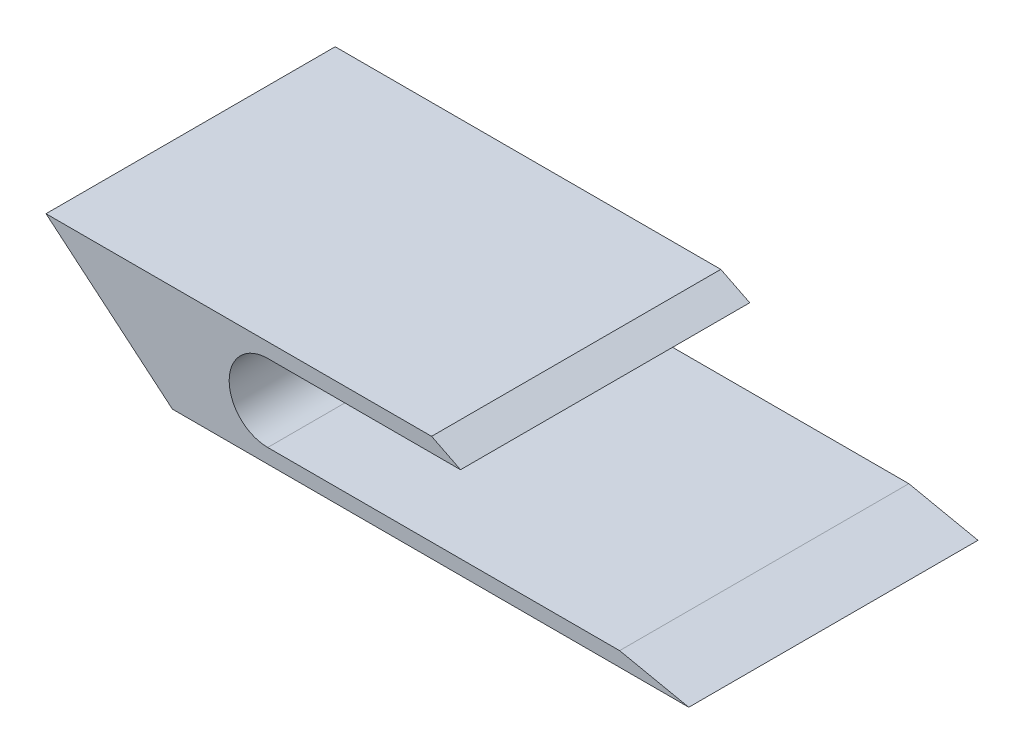
SolidWorks part; units mm, degrees
ref_plane "Front Plane" through (0, 0, 0) normal (0, 0, 1) x (1, 0, 0)
ref_plane "Top Plane" through (0, 0, 0) normal (0, 1, 0) x (1, 0, 0)
ref_plane "Right Plane" through (0, 0, 0) normal (1, 0, 0) x (0, 0, -1)
sketch "Sketch1" plane through (0, 0, 0) normal (0, 0, 1) x (1, 0, 0)
  line L0 (0, 4) -> (20, 4)
  line L1 (0, -4) -> (36.5036, -4)
  line L3 (43.6796, -5.5) -> (-9.8911, -5.5)
  line L6 (16.9996, 5.5) -> (-23.0004, 5.5)
  line L9 (43.6796, -5.5) -> (36.5036, -4)
  line L10 (16.9996, 5.5) -> (20, 4)
  line L11 (-23.0004, 5.5) -> (-9.8911, -5.5)
  arc A0 (0, 4) -> (0, -4) centre (0, 0) ccw
  point P5 (-4, 0)
  point P6 (0, 0)
  point P12 (-10.0399, -5.5)
  dimension "D1" = 40
  dimension "D5" = 1.5
  dimension "D2" = 53.5707
  dimension "D3" = 1.5
  dimension "D4" = 8
  dimension "D6" = 20
  dimension "D7" = 36.5036
  dimension "D8" = 8
  dimension "D9" = 140
extrude "Boss-Extrude1" add sketch "Sketch1" along normal blind 30
ref_plane "Plane1" through (-3, 0, 0) normal (1, 0, 0) x (0, 0, -1)
sketch "Sketch2" plane through (-3, 0, 0) normal (1, 0, 0) x (0, 0, -1)
  line L0 (-30, 5.5) -> (0, 5.5) construction
  line L1 (-30, -5.5) -> (0, -5.5) construction
  line L2 (0, 5.5) -> (0, -5.5) construction
  circle A0 centre (15, 0) radius 2.5
  dimension "D1" = 5
  dimension "D2" = 11
  dimension "D3" = 15
extrude "Boss-Extrude2" [suppressed] add sketch "Sketch2" against normal blind 30 separate body
